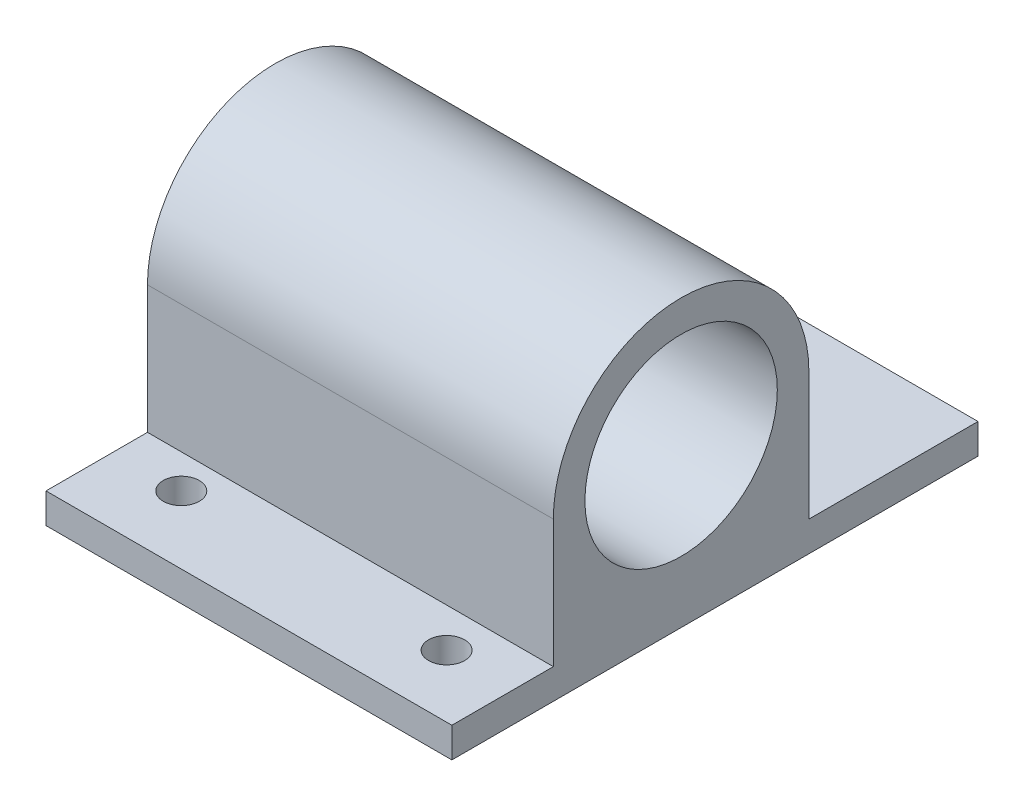
SolidWorks part; units mm, degrees
ref_plane "Front Plane" through (0, 0, 0) normal (0, 0, 1) x (1, 0, 0)
ref_plane "Top Plane" through (0, 0, 0) normal (0, 1, 0) x (1, 0, 0)
ref_plane "Right Plane" through (0, 0, 0) normal (1, 0, 0) x (0, 0, -1)
sketch "Sketch1" plane through (0, 0, 0) normal (0, 1, 0) x (1, 0, 0)
  line L1 (-10.0119, 14.0602) -> (11.9881, 14.0602)
  line L2 (-10.0119, 14.0602) -> (-10.0119, -15.9398)
  line L3 (-10.0119, -15.9398) -> (11.9881, -15.9398)
  line L4 (11.9881, 14.0602) -> (11.9881, -15.9398)
  line L5 (5.1381, -18.0598) -> (-3.1619, -18.0598)
  line L6 (5.1381, -18.0598) -> (5.1381, -13.8198)
  line L7 (5.1381, -13.8198) -> (-3.1619, -13.8198)
  line L8 (-3.1619, -18.0598) -> (-3.1619, -13.8198)
  line L9 (5.1381, -18.0598) -> (-3.1619, -13.8198) construction
  line L10 (5.1381, -13.8198) -> (-3.1619, -18.0598) construction
  line L11 (14.4881, -18.4398) -> (-12.5119, -18.4398)
  line L12 (14.4881, -18.4398) -> (14.4881, 16.5602)
  line L13 (14.4881, 16.5602) -> (-12.5119, 16.5602)
  line L14 (-12.5119, -18.4398) -> (-12.5119, 16.5602)
  line L15 (14.4881, -18.4398) -> (-12.5119, 16.5602) construction
  line L16 (14.4881, 16.5602) -> (-12.5119, -18.4398) construction
  circle A0 centre (-8.0119, 7.5602) radius 1.1746
  circle A1 centre (9.9881, 7.5602) radius 1.1992
  circle A2 centre (-8.0119, -13.9398) radius 1.1137
  circle A3 centre (9.9881, -14.2918) radius 1.0001
  point P12 (0.9881, -15.9398)
  point P17 (0.9881, -0.9398)
  dimension "D1" = 22
  dimension "D2" = 30
  dimension "D3" = 6.5
  dimension "D4" = 2
  dimension "D5" = 0
  dimension "D6" = 2
  dimension "D7" = 21.5
  dimension "D8" = 2.12
  dimension "D9" = 8.3
  dimension "D10" = 2.5
  dimension "D11" = 2.5
  dimension "D12" = 2.5
  dimension "D13" = 2.5
  dimension "D14" = 0
extrude "Boss-Extrude1" add sketch "Sketch1" along normal blind 2 contours L14 L11 L12 L13 L5 L8 L3 L2 L1 L4 L6 | L3 L8 L7 L6 L4 L1 L2 A3 A2 A1 A0 | A0 | A1 | A3 | L8 L5 L6 L3 | L8 L3 L6 L7 | A2
sketch "Sketch6" plane through (0, 2, 0) normal (0, 1, 0) x (1, 0, 0)
  line L11 (-12.5119, 16.5602) -> (14.4881, 16.5602)
  line L12 (-12.5119, 16.5602) -> (-12.5119, -18.4398)
  line L13 (-12.5119, -18.4398) -> (14.4881, -18.4398)
  line L14 (12.9881, -16.9398) -> (12.9881, 15.0602)
  line L15 (-11.0119, -16.9398) -> (12.9881, -16.9398)
  line L16 (-11.0119, 15.0602) -> (-11.0119, -16.9398)
  line L17 (12.9881, 15.0602) -> (-11.0119, 15.0602)
  line L18 (12.9881, -16.9398) -> (12.9881, 15.0602)
  line L19 (-11.0119, -16.9398) -> (12.9881, -16.9398)
  line L20 (-11.0119, 15.0602) -> (-11.0119, -16.9398)
  line L21 (12.9881, 15.0602) -> (-11.0119, 15.0602)
  line L22 (14.4881, 16.5602) -> (14.4881, -18.4398)
  dimension "D1" = 1.5
sketch "Sketch7" [suppressed] plane through (0, 0, 18.4398) normal (0, 0, 1) x (1, 0, 0)
  line L0 (-12.5119, 10.32) -> (14.4881, 10.32) construction
  line L1 (-3.2619, 10.32) -> (5.2381, 10.32)
  line L2 (-3.2619, 10.32) -> (-3.2619, 2.5)
  line L3 (-3.2619, 2.5) -> (5.2381, 2.5)
  line L4 (5.2381, 10.32) -> (5.2381, 2.5)
  line L5 (11.9881, 4) -> (7.9881, 4) construction
  dimension "D1" = 0
  dimension "D2" = 0
  dimension "D3" = 1.5
hole_wizard "M2 Clearance Hole2" positions "Sketch8" profile "Sketch9" hole size "M2" standard "ANSI Metric" end condition through all
sketch "Sketch8" plane through (0, 2, 0) normal (0, 1, 0) x (1, 0, 0)
  point P0 (-8.0119, 7.5602)
  point P3 (9.9881, 7.5602)
  point P6 (-8.0119, -13.9398)
  point P9 (9.9881, -14.2918)
sketch "Sketch9" plane through (-8.0119, 2, -7.5602) normal (1, 0, 0) x (0, 0, 1)
  line L0 (0, 0) -> (0, 2)
  line L1 (0, 2) -> (1.2, 2)
  line L2 (1.2, 2) -> (1.2, 0)
  line L5 (1.2, 0) -> (0, 0)
  line L11 (0, -6.35) -> (0, 107.95) construction
  dimension "Thru Hole Dia." = 2.4
  dimension "Thru Hole Depth" = 2
sketch "Sketch13" plane through (0, 2, 0) normal (0, 1, 0) x (1, 0, 0)
  line L0 (14.4881, -18.4398) -> (14.4881, 16.5602) construction
  line L1 (14.4881, -11.6898) -> (-12.5119, -11.6898)
  line L2 (14.4881, -11.6898) -> (14.4881, 5.3102)
  line L3 (14.4881, 5.3102) -> (-12.5119, 5.3102)
  line L4 (-12.5119, -11.6898) -> (-12.5119, 5.3102)
  line L5 (-12.5119, -18.4398) -> (-12.5119, 16.5602) construction
  circle A0 centre (-8.0119, -13.9398) radius 1.1137 construction
  dimension "D1" = 17
  dimension "D2" = 2.25
extrude "Boss-Extrude6" add sketch "Sketch13" along normal blind 17
sketch "Sketch14" plane through (14.4881, 0, 0) normal (1, 0, 0) x (0, 0, -1)
  line L0 (5.3102, 19) -> (5.3102, 2) construction
  line L1 (-11.6898, 19) -> (5.3102, 19) construction
  line L3 (-11.6898, 19) -> (5.3102, 19)
  line L4 (-11.6898, 19) -> (-11.6898, 2)
  line L5 (-11.6898, 2) -> (5.3102, 2)
  line L6 (5.3102, 19) -> (5.3102, 2)
  circle A0 centre (-3.1898, 10.5) radius 6.4
  circle A1 centre (-3.1898, 10.5) radius 8.5
  point P4 (5.3102, 10.5)
  point P7 (-3.1898, 19)
  line M6 (5.3102, 19) -> (-11.6898, 19)
  line M7 (-11.6898, 19) -> (-11.6898, 2)
  dimension "D3" = 12.8
  dimension "D1" = 0
  dimension "D2" = 0
extrude "Cut-Extrude3" cut sketch "Sketch14" against normal through all contours A0 | A1 L6 M6 | A1 L3 M7
sketch "Sketch10" plane through (0, 2, 0) normal (0, 1, 0) x (1, 0, 0)
  line L0 (11.9881, 14.0602) -> (11.9881, -15.9398) construction
  line L1 (6.4381, 2.0902) -> (-4.5619, 2.0902)
  line L2 (6.4381, 2.0902) -> (6.4381, 13.0902)
  line L3 (6.4381, 13.0902) -> (-4.5619, 13.0902)
  line L4 (-4.5619, 2.0902) -> (-4.5619, 13.0902)
  line L5 (6.4381, 2.0902) -> (-4.5619, 13.0902) construction
  line L6 (6.4381, 13.0902) -> (-4.5619, 2.0902) construction
  line L7 (-10.0119, 14.0602) -> (11.9881, 14.0602) construction
  point P0 (0.9381, 7.5902)
  dimension "D1" = 11
  dimension "D2" = 11
  dimension "D3" = 11.05
  dimension "D4" = 6.47
extrude "Cut-Extrude2" [suppressed] cut sketch "Sketch10" against normal up to next
fillet "Fillet1" [suppressed] radius 2
sketch "Sketch12" plane through (0, 2, 0) normal (0, 1, 0) x (1, 0, 0)
  line L0 (-3.1619, -18.0598) -> (-3.1619, -13.8198) construction
  line L1 (-3.1619, -18.4398) -> (5.1381, -18.4398)
  line L2 (-3.1619, -18.4398) -> (-3.1619, -16.9398)
  line L3 (-3.1619, -16.9398) -> (5.1381, -16.9398)
  line L4 (5.1381, -18.4398) -> (5.1381, -16.9398)
  line L5 (5.1381, -18.0598) -> (5.1381, -13.8198) construction
  line L6 (-11.0119, -16.9398) -> (12.9881, -16.9398) construction
  line L7 (14.4881, -18.4398) -> (-12.5119, -18.4398) construction
  dimension "D1" = 0
equation "\"D2@Sketch13\"=(21.5-17)/2"
